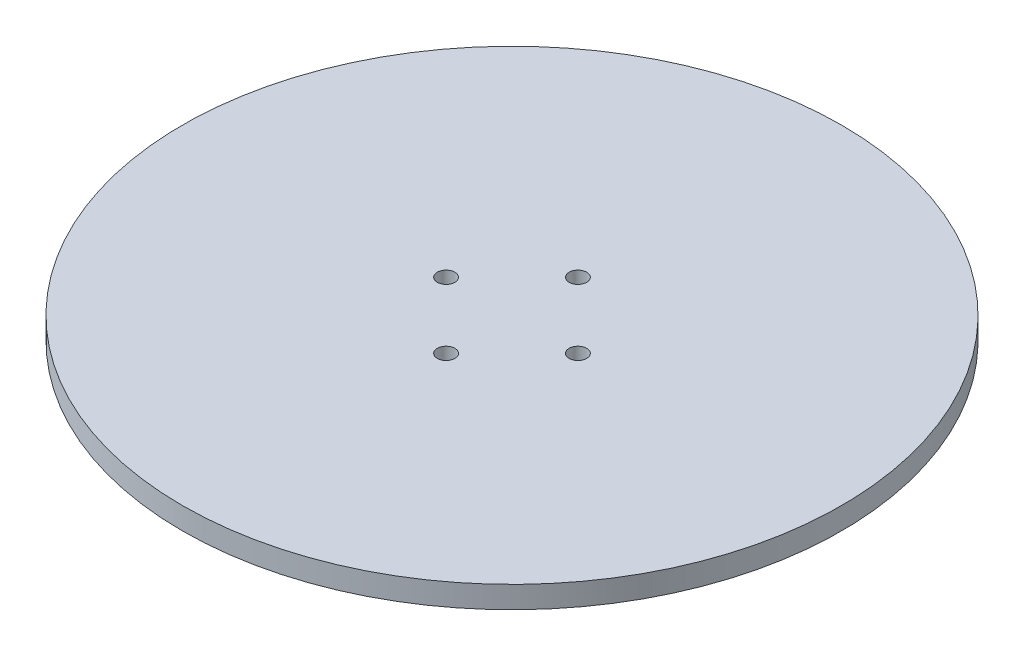
SolidWorks part; units mm, degrees
ref_plane "Front Plane" through (0, 0, 0) normal (0, 0, 1) x (1, 0, 0)
ref_plane "Top Plane" through (0, 0, 0) normal (0, 1, 0) x (1, 0, 0)
ref_plane "Right Plane" through (0, 0, 0) normal (1, 0, 0) x (0, 0, -1)
sketch "Sketch1" plane through (0, 0, 0) normal (0, 1, 0) x (1, 0, 0)
  circle A0 centre (0, 0) radius 75
  dimension "D1" = 150
extrude "Boss-Extrude1" add sketch "Sketch1" along normal blind 5
sketch "Sketch2" plane through (0, 5, 0) normal (0, 1, 0) x (1, 0, 0)
  line L0 (0, 0) -> (0, 15.6222) construction
  circle A0 centre (0, 0) radius 15 construction
  circle A2 centre (0, 15) radius 2
  dimension "D1" = 30
  dimension "D2" = 4
extrude "Cut-Extrude1" cut sketch "Sketch2" against normal up to next
pattern_circular "CirPattern1" count 4 over 360 about axis through (0, 0, 0) along (0, 1, 0) of "Cut-Extrude1"
